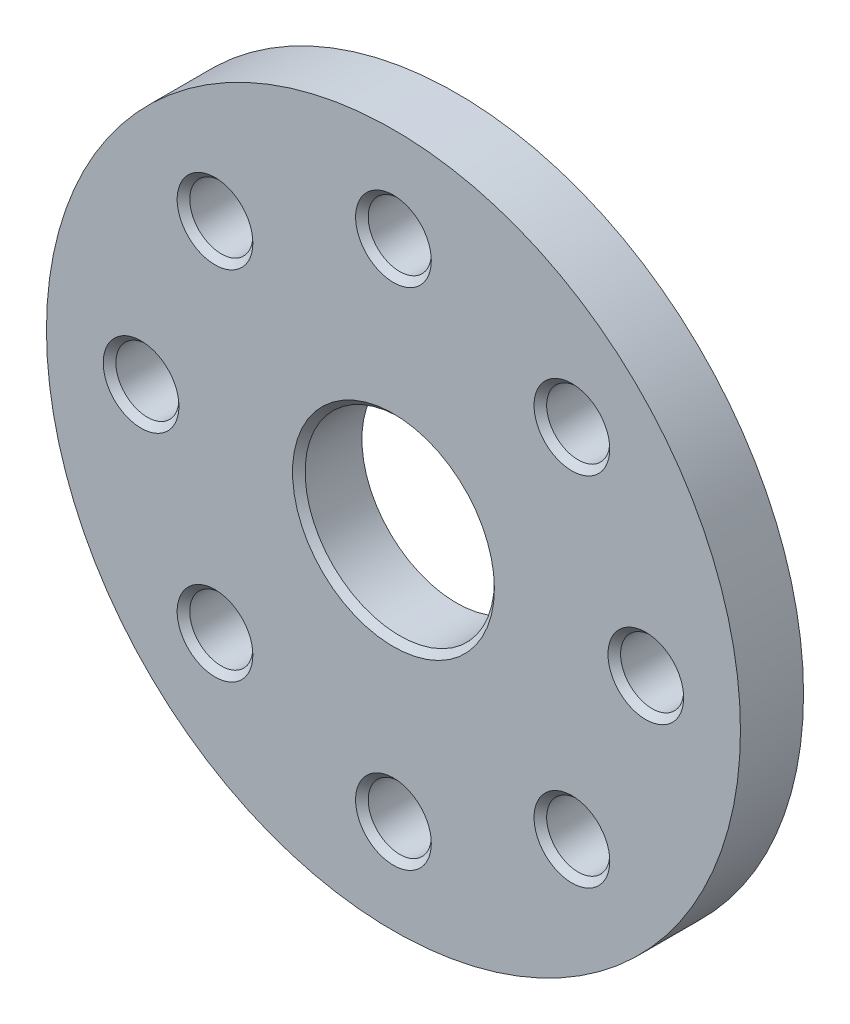
SolidWorks part; units mm, degrees
ref_plane "Front Plane" through (0, 0, 0) normal (0, 0, 1) x (1, 0, 0)
ref_plane "Top Plane" through (0, 0, 0) normal (0, 1, 0) x (1, 0, 0)
ref_plane "Right Plane" through (0, 0, 0) normal (1, 0, 0) x (0, 0, -1)
sketch "Sketch1" plane through (0, 0, 0) normal (0, 0, 1) x (1, 0, 0)
  circle A0 centre (0, 0) radius 11
  dimension "D1" = 22
extrude "Boss-Extrude1" add sketch "Sketch1" along normal blind 2
sketch "Sketch3" plane through (0, 0, 2) normal (0, 0, 1) x (1, 0, 0)
  circle A0 centre (0, 0) radius 3
extrude "Cut-Extrude1" cut sketch "Sketch3" against normal through all
sketch "Sketch4" plane through (0, 0, 2) normal (0, 0, 1) x (1, 0, 0)
  circle A0 centre (0, 8) radius 1
  dimension "D1" = 8
extrude "Cut-Extrude2" cut sketch "Sketch4" against normal through all
chamfer "Chamfer1" distance 0.2 angle 45 1 edges at (1, 8, 2)
chamfer "Chamfer2" distance 0.2 angle 45 1 edges at (3, 0, 2)
pattern_circular "CirPattern1" count 8 over 360 about axis through (0, 0, 0) along (0, 0, 1) of "Cut-Extrude2"
chamfer "Chamfer4" distance 0.2 angle 45 1 edges at (-6.364, -4.9497, 2)
chamfer "Chamfer5" distance 0.2 angle 45 2 edges at (8, -1, 2) (6.364, 4.9497, 2)
chamfer "Chamfer6" distance 0.2 angle 45 4 edges at (-4.9497, 6.364, 2) (-8, 1, 2) (-1, -8, 2) (4.9497, -6.364, 2)
